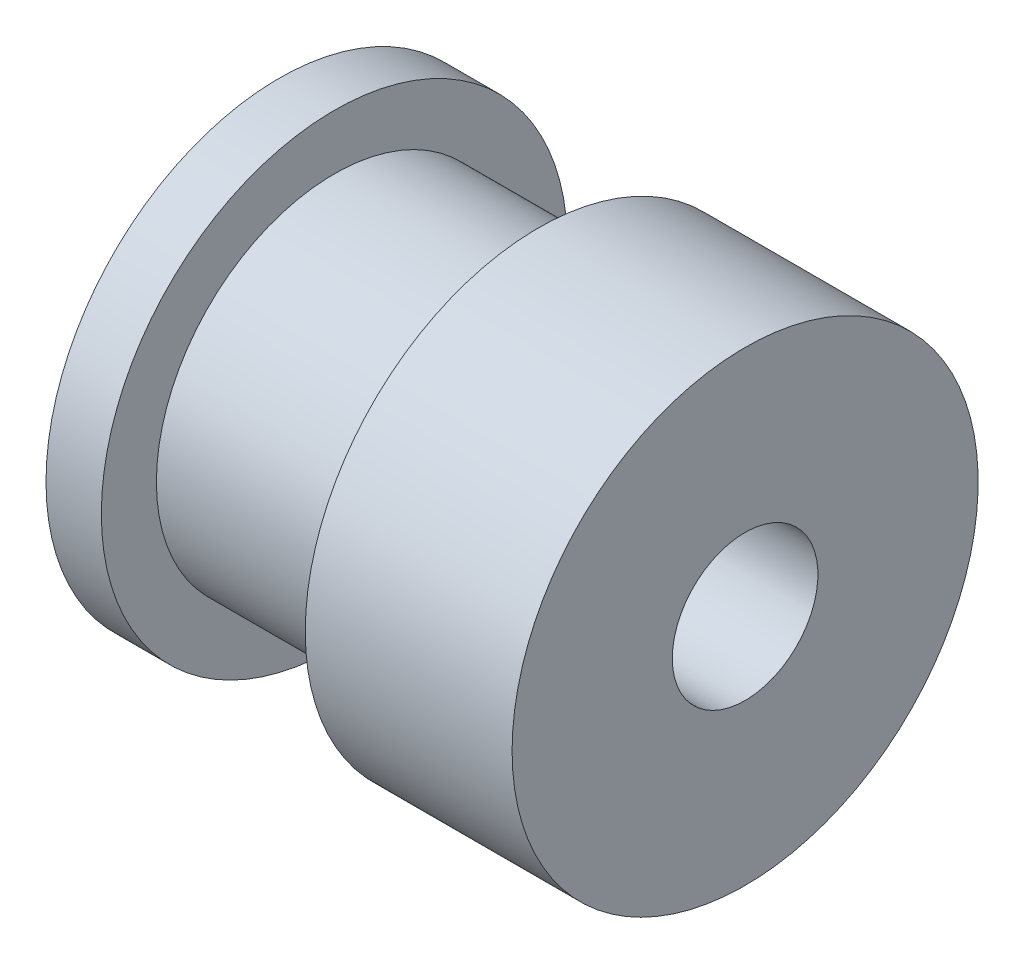
SolidWorks part; units mm, degrees
ref_plane "Front Plane" through (0, 0, 0) normal (0, 0, 1) x (1, 0, 0)
ref_plane "Top Plane" through (0, 0, 0) normal (0, 1, 0) x (1, 0, 0)
ref_plane "Right Plane" through (0, 0, 0) normal (1, 0, 0) x (0, 0, -1)
sketch "Sketch1" plane through (0, 0, 0) normal (0, 0, 1) x (1, 0, 0)
  line L0 (0, 0) -> (20.2857, 0) construction
  line L1 (0, -2.5) -> (0, -8)
  line L2 (0, -8) -> (1.9, -8)
  line L3 (1.9, -8) -> (1.9, -6.11)
  line L4 (1.9, -6.11) -> (8.9, -6.11)
  line L5 (8.9, -6.11) -> (8.9, -8)
  line L6 (8.9, -8) -> (16, -8)
  line L7 (16, -2.5) -> (16, -8)
  line L8 (0, -2.5) -> (16, -2.5)
  point P9 (12.45, -8)
  dimension "D1" = 16
  dimension "D2" = 7
  dimension "D3" = 7.1
  dimension "D4" = 8
  dimension "D5" = 6.11
  dimension "D6" = 2.5
revolve "Revolve1" add sketch "Sketch1" angle 360 about L0
